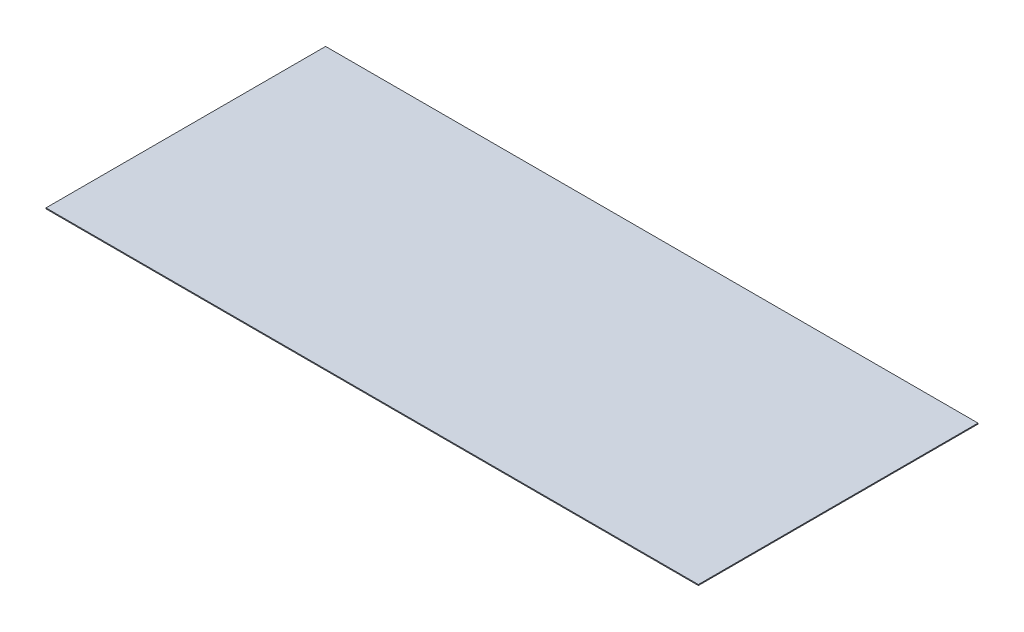
SolidWorks part; units mm, degrees
ref_plane "前视基准面" through (0, 0, 0) normal (0, 0, 1) x (1, 0, 0)
ref_plane "上视基准面" through (0, 0, 0) normal (0, 1, 0) x (1, 0, 0)
ref_plane "右视基准面" through (0, 0, 0) normal (1, 0, 0) x (0, 0, -1)
sketch "草图2" plane through (0, 0, 0) normal (0, 1, 0) x (1, 0, 0)
  line L1 (-7000, 3000) -> (7000, 3000)
  line L2 (-7000, 3000) -> (-7000, -3000)
  line L3 (-7000, -3000) -> (7000, -3000)
  line L4 (7000, 3000) -> (7000, -3000)
  line L5 (-7000, 3000) -> (7000, -3000) construction
  line L6 (-7000, -3000) -> (7000, 3000) construction
  point P0 (0, 0)
  dimension "D1" = 14000
  dimension "D2" = 6000
extrude "凸台-拉伸1" add sketch "草图2" against normal blind 20
